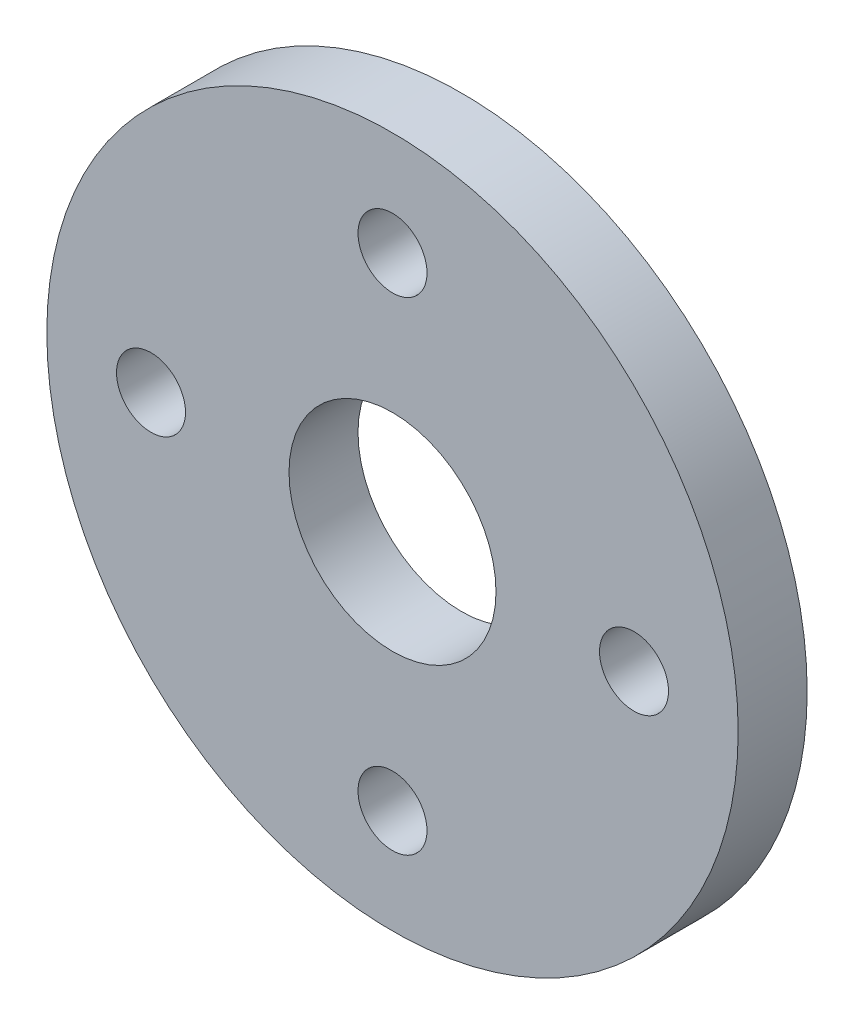
SolidWorks part; units mm, degrees
ref_plane "Front Plane" through (0, 0, 0) normal (0, 0, 1) x (1, 0, 0)
ref_plane "Top Plane" through (0, 0, 0) normal (0, 1, 0) x (1, 0, 0)
ref_plane "Right Plane" through (0, 0, 0) normal (1, 0, 0) x (0, 0, -1)
sketch "Sketch1" plane through (0, 0, 0) normal (0, 0, 1) x (1, 0, 0)
  circle A0 centre (0, 0) radius 10.02
  circle A1 centre (0, 0) radius 3
  circle A2 centre (0, 0) radius 7 construction
  circle A3 centre (0, 7) radius 1
  circle A4 centre (7, 0) radius 1
  circle A5 centre (0, -7) radius 1
  circle A6 centre (-7, 0) radius 1
  dimension "D1" = 20.04
  dimension "D2" = 6
  dimension "D3" = 14
  dimension "D5" = 2
  dimension "D4" = 4
extrude "Boss-Extrude1" add sketch "Sketch1" along normal blind 2
